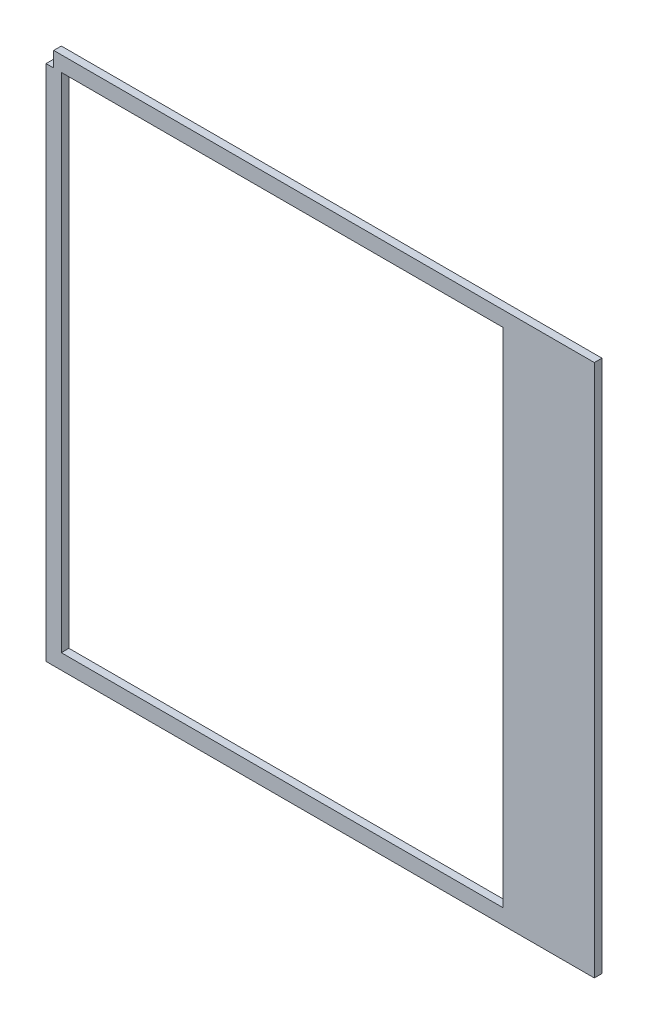
SolidWorks part; units mm, degrees
ref_plane "Alzado" through (0, 0, 0) normal (0, 0, 1) x (1, 0, 0)
ref_plane "Planta" through (0, 0, 0) normal (0, 1, 0) x (1, 0, 0)
ref_plane "Vista lateral" through (0, 0, 0) normal (1, 0, 0) x (0, 0, -1)
sketch "Croquis1" plane through (0, 0, 0) normal (0, 0, 1) x (1, 0, 0)
  line L1 (-156.5143, 244.4507) -> (198.4857, 244.4507)
  line L2 (-161.5143, 234.4507) -> (-161.5143, -105.5493)
  line L3 (-161.5143, -105.5493) -> (198.4857, -105.5493)
  line L4 (198.4857, 244.4507) -> (198.4857, -105.5493)
  line L5 (-161.5143, 234.4507) -> (-156.5143, 234.4507)
  line L8 (-156.5143, 234.4507) -> (-156.5143, 244.4507)
  line L9 (-151.5143, -95.5493) -> (138.4857, -95.5493)
  line L10 (-151.5143, -95.5493) -> (-151.5143, 234.4507)
  line L11 (-151.5143, 234.4507) -> (138.4857, 234.4507)
  line L12 (138.4857, -95.5493) -> (138.4857, 234.4507)
  dimension "D1" = 360
  dimension "D2" = 10
  dimension "D3" = 5
  dimension "D4" = 10
  dimension "D5" = 10
  dimension "D6" = 60
  dimension "D7" = 10
extrude "Saliente-Extruir1" add sketch "Croquis1" along normal blind 5
